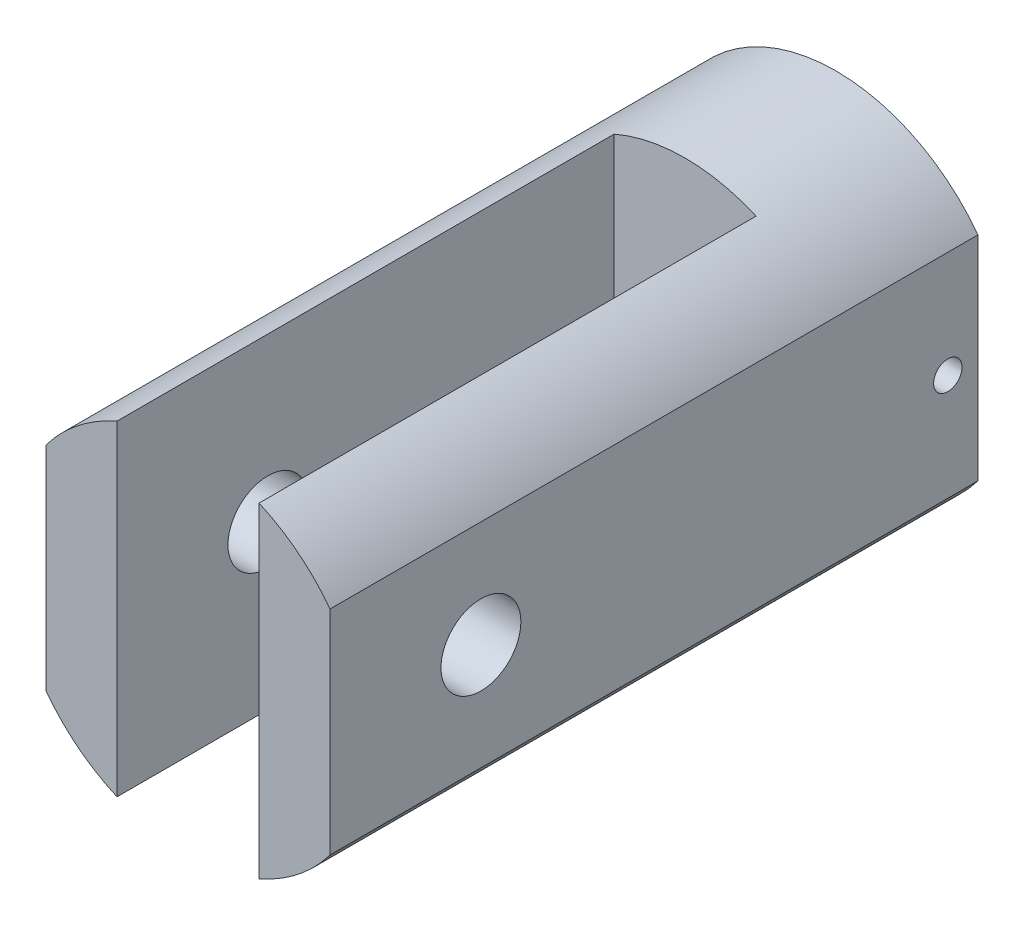
SolidWorks part; units mm, degrees
ref_plane "前视基准面" through (0, 0, 0) normal (0, 0, 1) x (1, 0, 0)
ref_plane "上视基准面" through (0, 0, 0) normal (0, 1, 0) x (1, 0, 0)
ref_plane "右视基准面" through (0, 0, 0) normal (1, 0, 0) x (0, 0, -1)
sketch "草图1" plane through (0, 0, 0) normal (0, 0, 1) x (1, 0, 0)
  circle A0 centre (0, 0) radius 10
extrude "凸台-拉伸2" add sketch "草图1" along normal blind 36.5 contours A0
sketch "草图3" plane through (0, 0, 0) normal (0, 1, 0) x (1, 0, 0)
  line L0 (0, 0) -> (0, -36.5) construction
  line L1 (-10, -36.5) -> (10, -36.5) construction
  line L2 (-4, -8.5) -> (4, -8.5)
  line L3 (4, -8.5) -> (4, -36.5)
  line L4 (4, -36.5) -> (-4, -36.5)
  line L5 (-4, -8.5) -> (-4, -36.5)
  point P10 (0, -8.5)
  dimension "D1" = 8
  dimension "D2" = 28
extrude "切除-拉伸1" cut sketch "草图3" against normal through all both and the other way through all
sketch "草图4" plane through (0, 0, 0) normal (0, 1, 0) x (1, 0, 0)
  line L0 (0, 0) -> (0, -40) construction
  line L1 (-10, -36.5) -> (-4, -36.5) construction
  line L2 (-10, 0) -> (-8, 0)
  line L3 (-10, 0) -> (-10, -36.5)
  line L4 (-10, -36.5) -> (-8, -36.5)
  line L5 (-8, 0) -> (-8, -36.5)
  line L6 (10, -36.5) -> (8, -36.5)
  line L7 (10, 0) -> (10, -36.5)
  line L8 (10, 0) -> (8, 0)
  line L9 (8, 0) -> (8, -36.5)
  dimension "D1" = 2
extrude "切除-拉伸2" cut sketch "草图4" against normal through all both and the other way through all
sketch "草图6" plane through (0, 0, 0) normal (1, 0, 0) x (0, 0, -1)
  line L0 (-36.5, 0) -> (0, 0) construction
  line L1 (-36.5, -6) -> (-36.5, 6) construction
  line L2 (0, 6) -> (0, -6) construction
  circle A0 centre (-28, 0) radius 2.25
  dimension "D1" = 28
  dimension "D2" = 4.5
extrude "切除-拉伸4" cut sketch "草图6" against normal through all both and the other way through all
sketch "草图7" plane through (0, 0, 0) normal (0, 0, -1) x (-1, 0, 0)
  circle A0 centre (0, 0) radius 2.85
  dimension "D1" = 5.7
extrude "切除-拉伸5" cut sketch "草图7" against normal blind 3.8
sketch "草图8" plane through (-8, 0, 0) normal (-1, 0, 0) x (0, 0, 1)
  line L0 (0, 0) -> (36.5, 0) construction
  line L1 (0, -6) -> (0, 6) construction
  line L2 (36.5, -6) -> (36.5, 6) construction
  circle A0 centre (1.7, 0) radius 0.8
  dimension "D1" = 1.6
  dimension "D2" = 1.7
extrude "切除-拉伸6" cut sketch "草图8" against normal through all
